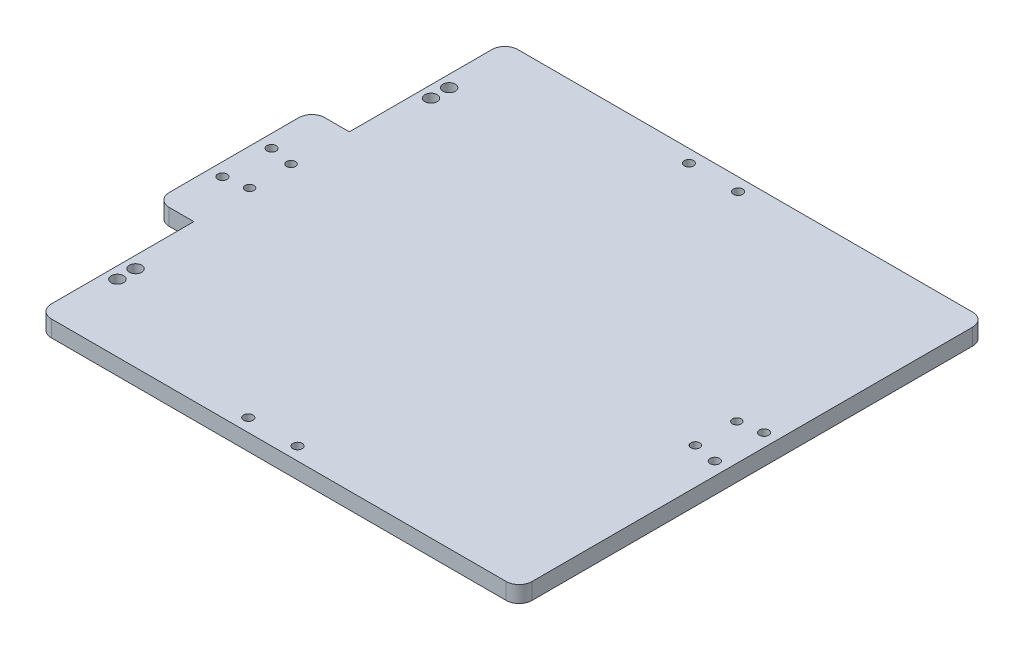
SolidWorks part; units mm, degrees
ref_plane "Front Plane" through (0, 0, 0) normal (0, 0, 1) x (1, 0, 0)
ref_plane "Top Plane" through (0, 0, 0) normal (0, 1, 0) x (1, 0, 0)
ref_plane "Right Plane" through (0, 0, 0) normal (1, 0, 0) x (0, 0, -1)
sketch "Sketch2" plane through (0, 0, 0) normal (0, 1, 0) x (1, 0, 0)
  line L0 (0, 90) -> (0, -90) construction
  line L1 (100, -90) -> (-100, -90)
  line L2 (100, -90) -> (100, 90)
  line L3 (100, 90) -> (-100, 90)
  line L4 (-100, -90) -> (-100, 90)
  line L5 (100, -90) -> (-100, 90) construction
  line L6 (100, 90) -> (-100, -90) construction
  line L7 (-100, 0) -> (100, 0) construction
  line L8 (-81, 90) -> (-81, 64) construction
  line L9 (-81, 64) -> (-81, 57) construction
  line L10 (-81, 64) -> (-85.5, 64) construction
  line L11 (-85.5, 90) -> (-85.5, 30.0041)
  line L12 (-85.5, 30.0041) -> (-100, 30.0041)
  line L13 (-85.5, -30.0041) -> (-100, -30.0041)
  line L14 (-85.5, -90) -> (-85.5, -30.0041)
  circle A0 centre (-9.5, 85) radius 1.8
  circle A1 centre (-9.5, -85) radius 1.8
  circle A2 centre (9.5, -85) radius 1.8
  circle A3 centre (9.5, 85) radius 1.8
  circle A4 centre (95, 9.5) radius 1.8
  circle A5 centre (95, -9.5) radius 1.8
  circle A6 centre (-95, 9.5) radius 1.8
  circle A7 centre (-95, -9.5) radius 1.8
  circle A8 centre (-86, 8) radius 1.7
  circle A9 centre (-86, -8) radius 1.7
  circle A10 centre (86, -8) radius 1.7
  circle A11 centre (86, 8) radius 1.7
  circle A12 centre (-81, 64) radius 2.3813
  circle A13 centre (-81, 57) radius 2.3813
  circle A14 centre (-81, -57) radius 2.3813
  circle A15 centre (-81, -64) radius 2.3813
  point P0 (0, 0)
  dimension "D3" = 3.6
  dimension "D4" = 9.5
  dimension "D5" = 5
  dimension "D6" = 3.6
  dimension "D7" = 9.5
  dimension "D8" = 5
  dimension "D9" = 3.4
  dimension "D10" = 14
  dimension "D11" = 16
  dimension "D14" = 4.7625
  dimension "D16" = 4.7625
  dimension "D1" = 200
  dimension "D2" = 180
  dimension "D12" = 26
  dimension "D13" = 19
  dimension "D15" = 7
  dimension "D17" = 4.5
extrude "Boss-Extrude1" add sketch "Sketch2" along normal blind 6.35 contours L11 L12 L4 L1 L2 L3 A13 A12 A9 A8 A7 A5 A4 A1 A0 A2 A3 A6 A10 A11
fillet "Fillet1" radius 5 6 edges at (-100, 3.175, -30.0041) (-85.5, 3.175, -90) (100, 3.175, -90) (100, 3.175, 90) (-85.5, 3.175, 90) (-100, 3.175, 30.0041)
